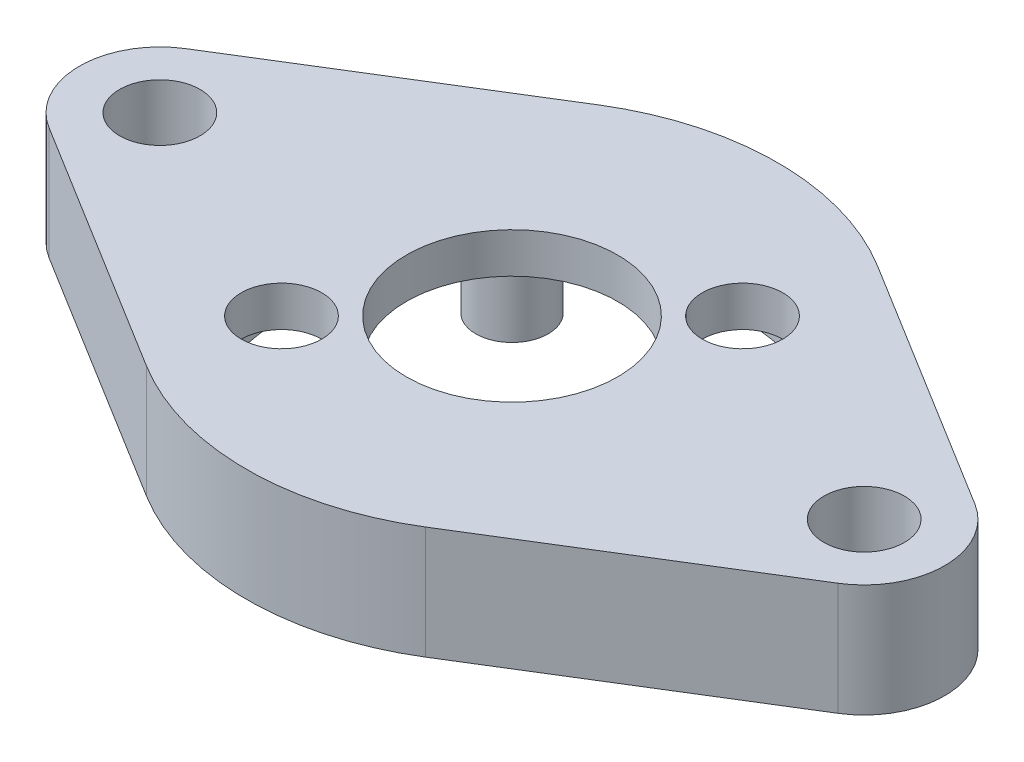
SolidWorks part; units mm, degrees
ref_plane "Front Plane" through (0, 0, 0) normal (0, 0, 1) x (1, 0, 0)
ref_plane "Top Plane" through (0, 0, 0) normal (0, 1, 0) x (1, 0, 0)
ref_plane "Right Plane" through (0, 0, 0) normal (1, 0, 0) x (0, 0, -1)
sketch "Sketch1" plane through (0, 0, 0) normal (0, 1, 0) x (1, 0, 0)
  line L0 (-6.9394, 11.2287) -> (-19.6029, 3.4026)
  line L1 (-19.6029, -3.4026) -> (-6.9394, -11.2287)
  line L2 (0, 0) -> (0, 11.2) construction
  line L3 (19.6029, -3.4026) -> (6.9394, -11.2287)
  line L4 (6.9394, 11.2287) -> (19.6029, 3.4026)
  circle A0 centre (0, 0) radius 11.2
  circle A1 centre (0, 0) radius 13.2
  arc A2 (-19.6029, 3.4026) -> (-19.6029, -3.4026) centre (-17.5, 0) ccw
  circle A3 centre (-17.5, 0) radius 2
  circle A4 centre (17.5, 0) radius 2
  arc A5 (19.6029, 3.4026) -> (19.6029, -3.4026) centre (17.5, 0) cw
  dimension "D1" = 4
  dimension "D2" = 22.4
  dimension "D3" = 2
  dimension "D4" = 4
  dimension "D5" = 17.5
extrude "Boss-Extrude1" add sketch "Sketch1" along normal blind 3.6 contours L0 A2 L1 A1 A3 | A1 A0 | A5 L4 A1 L3 A4
sketch "Sketch2" plane through (0, 3.6, 0) normal (0, 1, 0) x (1, 0, 0)
  line L5 (-6.9394, 11.2287) -> (-19.6029, 3.4026)
  line L6 (-19.6029, -3.4026) -> (-6.9394, -11.2287)
  line L7 (6.9394, -11.2287) -> (19.6029, -3.4026)
  line L8 (19.6029, 3.4026) -> (6.9394, 11.2287)
  line L9 (-6.9394, 11.2287) -> (-19.6029, 3.4026)
  line L10 (-19.6029, -3.4026) -> (-6.9394, -11.2287)
  line L11 (6.9394, -11.2287) -> (19.6029, -3.4026)
  line L12 (19.6029, 3.4026) -> (6.9394, 11.2287)
  circle A0 centre (-17.5, 0) radius 2 construction
  circle A1 centre (17.5, 0) radius 2 construction
  circle A2 centre (17.5, 0) radius 2
  circle A3 centre (-17.5, 0) radius 2
  circle A4 centre (0, 0) radius 5.25
  arc A6 (-19.6029, 3.4026) -> (-19.6029, -3.4026) centre (-17.5, 0) ccw
  arc A7 (-6.9394, -11.2287) -> (6.9394, -11.2287) centre (0, 0) ccw
  arc A8 (19.6029, -3.4026) -> (19.6029, 3.4026) centre (17.5, 0) ccw
  arc A9 (6.9394, 11.2287) -> (-6.9394, 11.2287) centre (0, 0) ccw
  arc A10 (-19.6029, 3.4026) -> (-19.6029, -3.4026) centre (-17.5, 0) ccw
  arc A11 (-6.9394, -11.2287) -> (6.9394, -11.2287) centre (0, 0) ccw
  arc A12 (19.6029, -3.4026) -> (19.6029, 3.4026) centre (17.5, 0) ccw
  arc A13 (6.9394, 11.2287) -> (-6.9394, 11.2287) centre (0, 0) ccw
  dimension "D2" = 10.5
  dimension "D1" = 0
extrude "Boss-Extrude2" add sketch "Sketch2" along normal blind 2
sketch "Sketch3" plane through (0, 5.6, 0) normal (0, 1, 0) x (1, 0, 0)
  line L0 (-9.5904, 9.5904) -> (9.5904, -9.5904) construction
  line L1 (-6.9394, 11.2287) -> (-19.6029, 3.4026) construction
  line L2 (6.9394, -11.2287) -> (19.6029, -3.4026) construction
  line L3 (9.5904, 9.5904) -> (-9.5904, -9.5904) construction
  line L4 (19.6029, 3.4026) -> (6.9394, 11.2287) construction
  line L5 (-19.6029, -3.4026) -> (-6.9394, -11.2287) construction
  circle A0 centre (5.7276, 5.7276) radius 2
  circle A1 centre (-5.7276, -5.7276) radius 2
  dimension "D1" = 4
  dimension "D3" = 8.1
  dimension "D2" = 8.1
extrude "Cut-Extrude1" cut sketch "Sketch3" against normal blind 2
sketch "Sketch4" plane through (0, 3.6, 0) normal (0, -1, 0) x (1, 0, 0)
  line L0 (-5.7276, 5.7276) -> (5.7276, -5.7276) construction
  line L1 (0, 0) -> (7.9196, 7.9196) construction
  circle A0 centre (0, 0) radius 11.2 construction
  circle A1 centre (5.7276, 5.7276) radius 1.8
  circle A2 centre (-5.7276, -5.7276) radius 1.8
  dimension "D1" = 3.6
  dimension "D2" = 8.1
extrude "Boss-Extrude3" add sketch "Sketch4" along normal up to surface (3.6 mm away) up to face at (-17.5, 0, 2)
